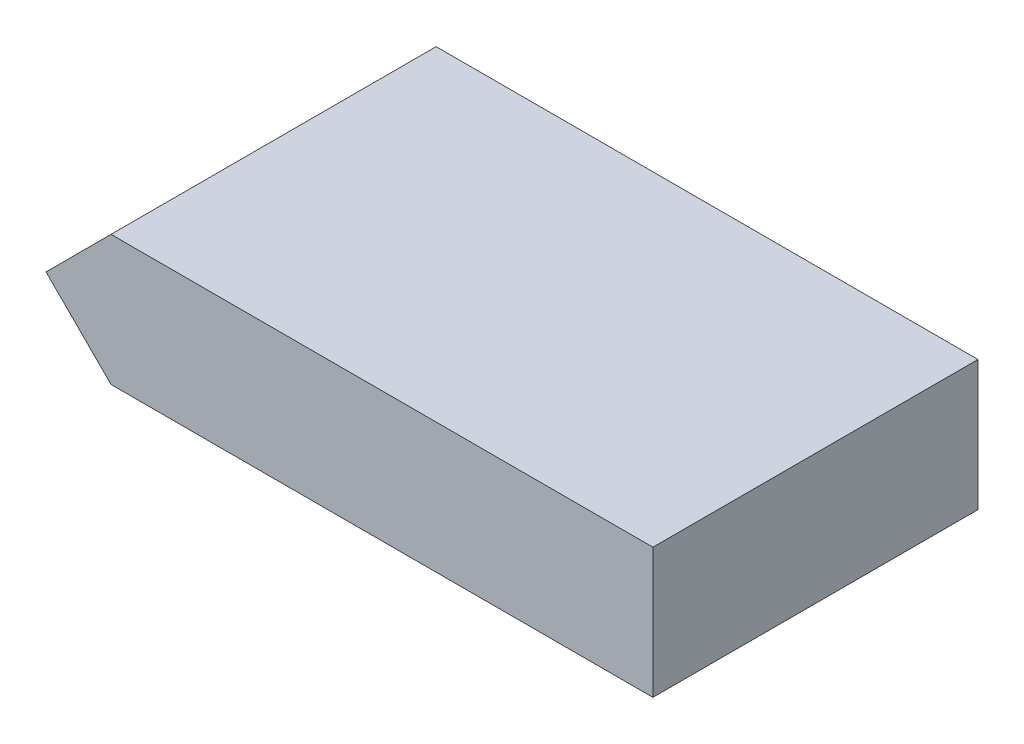
SolidWorks part; units mm, degrees
ref_plane "Front Plane" through (0, 0, 0) normal (0, 0, 1) x (1, 0, 0)
ref_plane "Top Plane" through (0, 0, 0) normal (0, 1, 0) x (1, 0, 0)
ref_plane "Right Plane" through (0, 0, 0) normal (1, 0, 0) x (0, 0, -1)
sketch "Sketch1" plane through (0, 0, 0) normal (0, 0, 1) x (1, 0, 0)
  line L0 (0, 0) -> (6, 6)
  line L1 (6, 6) -> (56, 6)
  line L2 (56, 6) -> (56, -6)
  line L3 (0, 0) -> (56, 0) construction
  line L4 (6, -6) -> (56, -6)
  line L5 (0, 0) -> (6, -6)
  dimension "D1" = 45
  dimension "D2" = 50
  dimension "D3" = 6
extrude "Boss-Extrude1" add sketch "Sketch1" along normal mid plane 30
